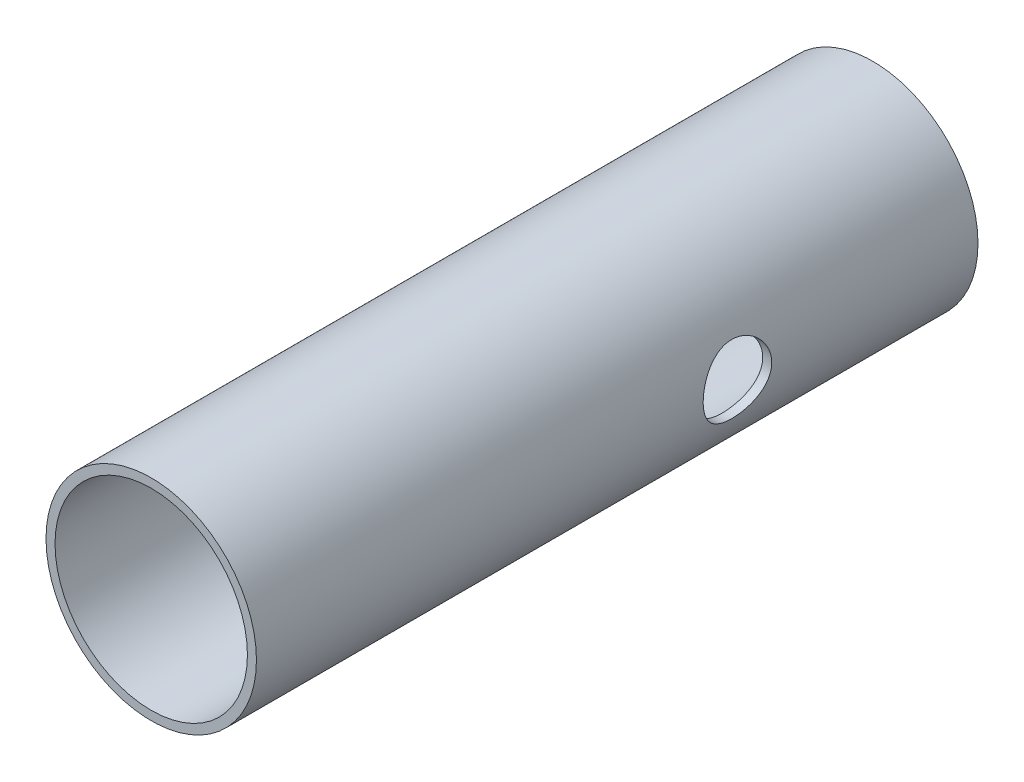
SolidWorks part; units mm, degrees
material "ABS"
ref_plane "Front Plane" through (0, 0, 0) normal (1, 0, 0) x (0, 1, 0)
ref_plane "Top Plane" through (0, 0, 0) normal (0, 0, 1) x (0, 1, 0)
ref_plane "Right Plane" through (0, 0, 0) normal (0, 1, 0) x (-1, 0, 0)
sketch "Sketch1" plane through (0, 0, 0) normal (0, 0, 1) x (0, 1, 0)
  circle A0 centre (0, 0) radius 44.45
  circle A1 centre (0, 0) radius 40.64
  dimension "D1" = 88.9
  dimension "D2" = 81.28
extrude "Boss-Extrude1" add sketch "Sketch1" along normal blind 304.8
sketch "Sketch2" plane through (0, 0, 0) normal (1, 0, 0) x (0, 1, 0)
  line L0 (-44.45, 0) -> (44.45, 0) construction
  circle A0 centre (0, 101.6) radius 14.478
  dimension "D2" = 28.956
  dimension "D1" = 101.6
extrude "Cut-Extrude1" cut sketch "Sketch2" against normal through all both and the other way through all
equation "\"D1@Sketch1\"=\"Body_OD\""
equation "\"D2@Sketch1\"=\"Body_ID\""
equation "\"D1@Boss-Extrude1\" = \"Body_Height\""
equation "\"D1@Sketch2\"=\"Pivot_Height\""
equation "\"D2@Sketch2\"=\"Body_Bearing_Hole_OD\""
equation "\"Body_OD\" = 3.5in"
equation "\"Body_ID\" = 3.2in"
equation "\"Body_Height\" = 12in"
equation "\"Bearing_OD\" = 1.13in"
equation "\"Bearing_ID\" = 0.5in"
equation "\"Body_Bearing_Hole_OD\" = \"Bearing_OD\" + 0.01in 'with clearance"
equation "\"Pivot_Height\" = 4in 'measured from bottom of tube"
equation "\"Pivot_OD\" = \"Bearing_ID\" - 0.01in 'with clearance"
